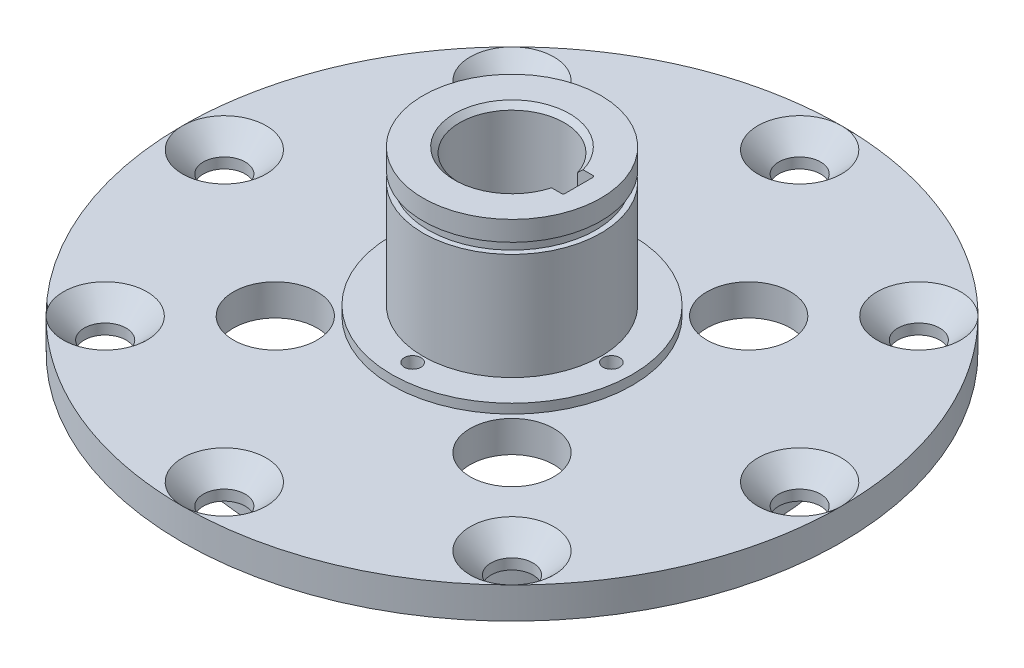
SolidWorks part; units mm, degrees
material "7075-T6 (SN)"
ref_plane "前视基准面" through (0, 0, 0) normal (0, 0, 1) x (1, 0, 0)
ref_plane "上视基准面" through (0, 0, 0) normal (0, 1, 0) x (1, 0, 0)
ref_plane "右视基准面" through (0, 0, 0) normal (1, 0, 0) x (0, 0, -1)
sketch "草图1" plane through (0, 0, 0) normal (0, 0, 1) x (1, 0, 0)
  line L0 (-45.0495, 0) -> (46.6176, 0) construction
  line L1 (0, 57.0959) -> (0, -46.8315) construction
  line L2 (24.5, 0) -> (31.5, 0)
  line L3 (31.5, 0) -> (31.5, 3)
  line L4 (31.5, 3) -> (11.5, 3)
  line L5 (11.5, 3) -> (11.5, 3.9)
  line L6 (11.5, 3.9) -> (8.5, 3.9)
  line L7 (8.5, 3.9) -> (8.5, 14.1)
  line L8 (8.5, 14.1) -> (8, 14.1)
  line L11 (5, 15.1) -> (5, 0)
  line L12 (24.5, 0) -> (24.5, -2)
  line L13 (24.5, -2) -> (20, -2)
  line L14 (5, 0) -> (20, 0)
  line L15 (20, 0) -> (20, -2)
  line L17 (5, 15.1) -> (8, 15.1)
  line L18 (8, 15.1) -> (8, 14.1)
  dimension "D2" = 3
  dimension "D3" = 23
  dimension "D4" = 17
  dimension "D5" = 0.9
  dimension "D6" = 10.2
  dimension "D7" = 1
  dimension "D8" = 16
  dimension "D9" = 10
  dimension "D10" = 49
  dimension "D11" = 2
  dimension "D12" = 40
  dimension "D13" = 3.9
  dimension "D14" = 7
revolve "旋转1" add sketch "草图1" angle 360 about L1
sketch "草图2" plane through (0, 3, 0) normal (0, -1, 0) x (1, 0, 0)
  line L0 (0, 37.1524) -> (0, -32.9469) construction
  point P3 (0, 27.5)
  point P4 (0, -27.5)
  point P5 (-19.4454, -19.4454)
  point P6 (-27.5, 0)
  point P7 (19.4454, 19.4454)
  point P8 (27.5, 0)
  point P9 (19.4454, -19.4454)
  point P10 (0, 0)
  point P11 (-19.4454, 19.4454)
  dimension "D1" = 27.5
  dimension "D2" = 8
hole_wizard "打孔尺寸(%根据十字)槽半沉头木螺钉的类型1" positions "草图3" profile "草图4" countersink size "M4" standard "GB" end condition through all
sketch "草图3" plane through (0, 3, 0) normal (0, -1, 0) x (-1, 0, 0)
  point P0 (0, -27.5)
  point P3 (-19.4454, 19.4454)
  point P6 (-27.5, 0)
  point P9 (-19.4454, -19.4454)
  point P12 (0, 27.5)
  point P15 (19.4454, 19.4454)
  point P18 (27.5, 0)
  point P21 (19.4454, -19.4454)
sketch "草图4" plane through (0, 3, 27.5) normal (1, 0, 0) x (0, 0, 1)
  line L0 (0, 0) -> (0, 5)
  line L1 (0, 5) -> (2, 5)
  line L2 (2, 5) -> (2, 2)
  line L3 (2, 2) -> (4, 0)
  line L5 (4, 0) -> (0, 0)
  line L6 (-2, 2) -> (-4, 0) construction
  line L11 (0, -6.35) -> (0, 107.95) construction
  dimension "通孔孔直径" = 4
  dimension "通孔孔深度" = 5
  dimension "近端锥形沉头孔直径" = 8
  dimension "近端锥形沉头孔角度" = 90
sketch "草图7" plane through (0, 15.1, 0) normal (0, 1, 0) x (1, 0, 0)
  line L0 (0, 14.5451) -> (0, -21.0085) construction
  line L1 (23.2104, 0) -> (-18.8727, 0) construction
  line L2 (6.4, -1.5) -> (6.4, 1.5)
  line L3 (6.4, 1.5) -> (4.7697, 1.5)
  line L4 (6.4, -1.5) -> (4.7697, -1.5)
  arc A1 (4.7697, -1.5) -> (4.7697, 1.5) centre (0, 0) ccw
  circle A3 centre (0, 0) radius 5 construction
  point P12 (6.4, 0)
  dimension "D1" = 6.4
  dimension "D2" = 3
extrude "切除-拉伸1" cut sketch "草图7" against normal through all
sketch "草图12" plane through (0, 15.1, 0) normal (0, 1, 0) x (1, 0, 0)
  line L0 (6.4, 1.5) -> (4.7697, 1.5) construction
  line L1 (6.4, 1.5) -> (4.7697, 1.5)
  line L2 (6.4, -1.5) -> (6.4, 1.5) construction
  line L3 (6.4, -1.5) -> (6.4, 1.5)
  line L4 (4.7697, -1.5) -> (6.4, -1.5) construction
  line L5 (4.7697, -1.5) -> (6.4, -1.5)
  arc A0 (4.7697, 1.5) -> (4.7697, -1.5) centre (0, 0) ccw construction
  arc A1 (4.7697, 1.5) -> (4.7697, -1.5) centre (0, 0) ccw
  circle A3 centre (0, 0) radius 8.5
  circle A4 centre (0, 0) radius 8.5 construction
extrude "凸台-拉伸1" add sketch "草图12" along normal blind 1.9
fillet "圆角2" radius 0.15 2 edges at (6.4, 8.5, 1.5) (6.4, 8.5, -1.5)
chamfer "倒角3" distance 0.5 angle 45 2 edges at (-5, 0, 0) (-5, 17, 0)
sketch "草图8" plane through (0, 3.9, 0) normal (0, 1, 0) x (1, 0, 0)
  circle A0 centre (0, 0) radius 9.5 construction
  point P3 (9.5, 0)
  point P7 (0, -9.5)
  point P8 (-9.5, 0)
  point P9 (0, 9.5)
  point P10 (0, 0)
  dimension "D1" = 19
  dimension "D2" = 4
hole_wizard "M2 螺纹孔1" positions "草图9" profile "草图10" tap size "M2" standard "GB" end condition through all
sketch "草图9" plane through (0, 3.9, 0) normal (0, 1, 0) x (1, 0, 0)
  point P0 (9.5, 0)
  point P4 (0, -9.5)
  point P7 (0, 9.5)
  point P10 (-9.5, 0)
sketch "草图10" plane through (9.5, 3.9, 0) normal (1, 0, 0) x (0, 0, 1)
  line L0 (0, 0) -> (0, 5.9)
  line L1 (0, 5.9) -> (0.8, 5.9)
  line L2 (0.8, 5.9) -> (0.8, 0)
  line L5 (0.8, 0) -> (0, 0)
  line L11 (0, -6.35) -> (0, 107.95) construction
  dimension "通孔螺纹孔钻头直径" = 1.6
  dimension "通孔螺纹孔钻头深度" = 5.9
cosmetic thread "孔螺蚊线1" parameters "D2"=2
cosmetic thread "孔螺蚊线2" parameters "D2"=2
cosmetic thread "孔螺蚊线3" parameters "D2"=2
cosmetic thread "孔螺蚊线4" parameters "D2"=2
sketch "草图11" plane through (0, 3, 0) normal (0, 1, 0) x (1, 0, 0)
  line L0 (21.3902, 0) -> (-13.545, 0) construction
  line L1 (0, 19.4745) -> (0, -21.7741) construction
  line L2 (11.3137, 11.3137) -> (0, 0) construction
  circle A0 centre (11.3137, 11.3137) radius 4
  circle A1 centre (11.3137, -11.3137) radius 4
  circle A2 centre (-11.3137, -11.3137) radius 4
  circle A3 centre (-11.3137, 11.3137) radius 4
  point P16 (0, 0)
  dimension "D1" = 8
  dimension "D3" = 32
  dimension "D4" = 45
  dimension "D2" = 4
extrude "切除-拉伸2" cut sketch "草图11" against normal through all
move or copy body "实体-移动/复制1" [suppressed] bodies to move or copy 110
